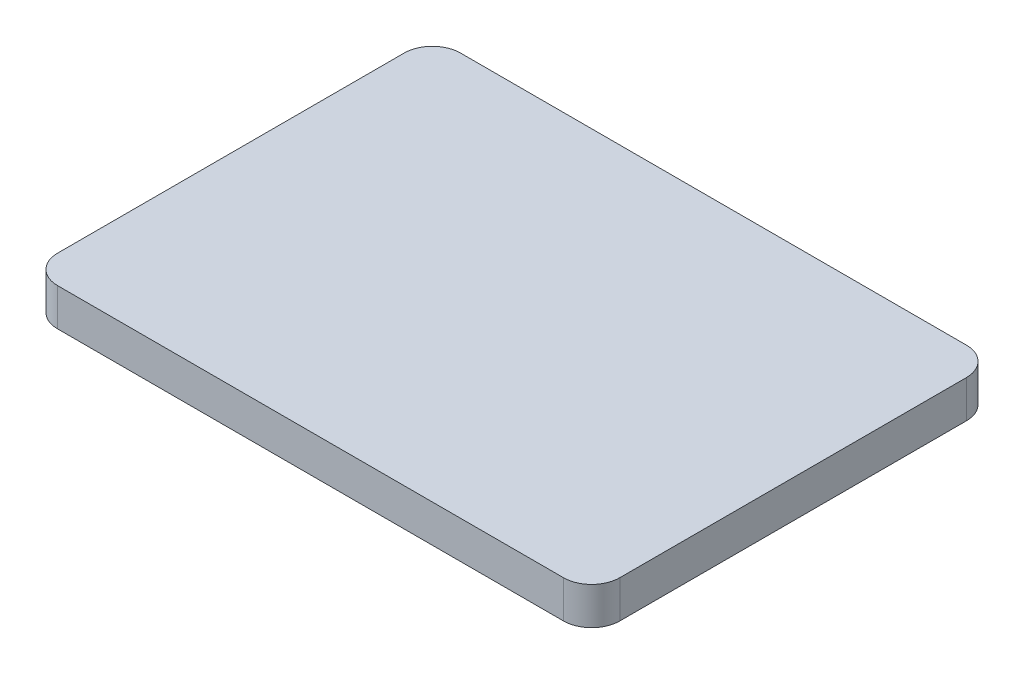
SolidWorks part; units mm, degrees
material "ﾆﾄﾘﾙｺﾞﾑ(NBR)"
ref_plane "正面" through (0, 0, 0) normal (0, 0, 1) x (1, 0, 0)
ref_plane "平面" through (0, 0, 0) normal (0, 1, 0) x (1, 0, 0)
ref_plane "右側面" through (0, 0, 0) normal (1, 0, 0) x (0, 0, -1)
sketch "ｽｹｯﾁ1" plane through (0, 0, 0) normal (0, 1, 0) x (1, 0, 0)
  line L0 (0, 0) -> (60, 0)
  line L1 (60, 0) -> (60, 43)
  line L2 (60, 43) -> (0, 43)
  line L3 (0, 43) -> (0, 0)
extrude "ﾎﾞｽ - 押し出し1" add sketch "ｽｹｯﾁ1" along normal blind 4
fillet "ﾌｨﾚｯﾄ1" radius 3 4 edges at (0, 2, -43) (60, 2, -43) (60, 2, 0) (0, 2, 0)
